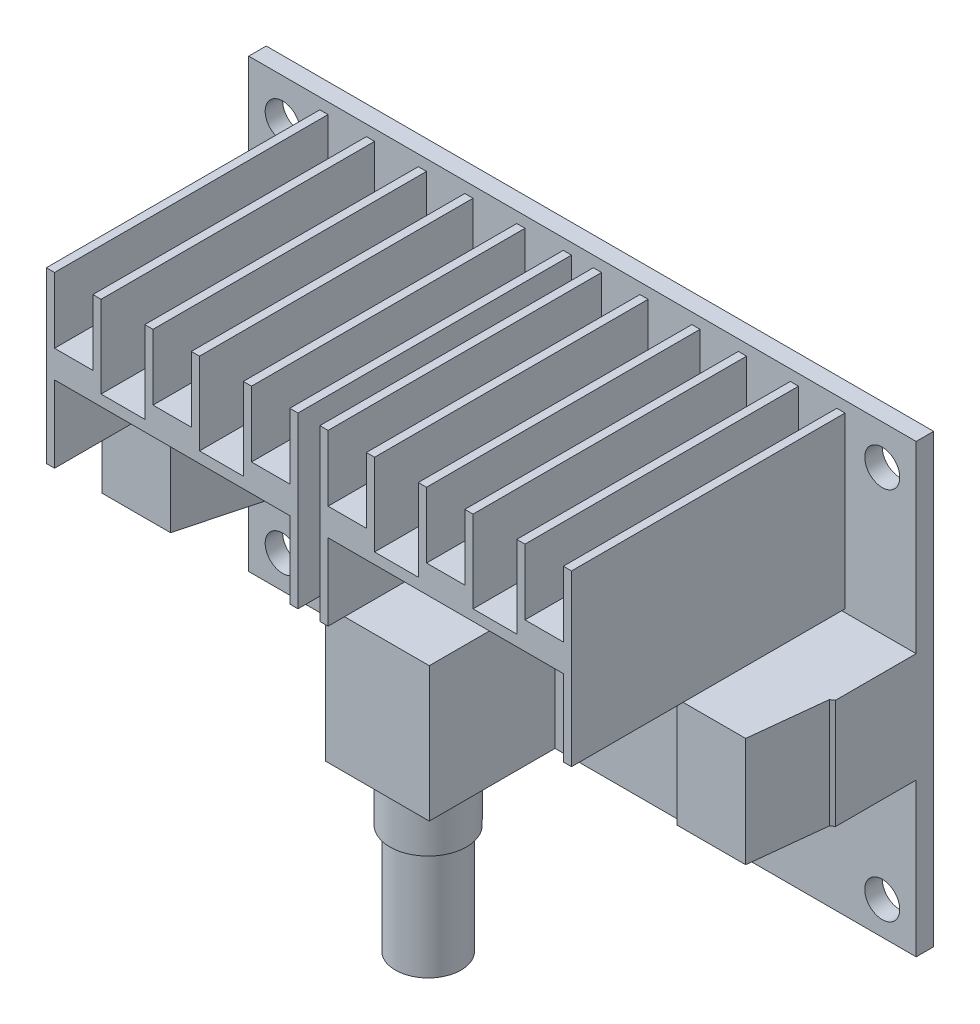
SolidWorks part; units mm, degrees
ref_plane "Front Plane" through (0, 0, 0) normal (0, 0, 1) x (1, 0, 0)
ref_plane "Top Plane" through (0, 0, 0) normal (0, 1, 0) x (1, 0, 0)
ref_plane "Right Plane" through (0, 0, 0) normal (1, 0, 0) x (0, 0, -1)
sketch "Sketch2" plane through (0, 0, 0) normal (0, 0, 1) x (1, 0, 0)
  line L1 (-30.5, -20.4) -> (30.5, -20.4)
  line L2 (-30.5, -20.4) -> (-30.5, 20.4)
  line L3 (-30.5, 20.4) -> (30.5, 20.4)
  line L4 (30.5, -20.4) -> (30.5, 20.4)
  line L5 (-30.5, -20.4) -> (30.5, 20.4) construction
  line L6 (-30.5, 20.4) -> (30.5, -20.4) construction
  circle A0 centre (-27.4, 16.8) radius 1.6
  circle A1 centre (27.4, 16.8) radius 1.6
  circle A2 centre (-27.4, -17.4) radius 1.6
  circle A3 centre (27.4, -17.4) radius 1.6
  point P0 (0, 0)
  dimension "D3" = 3.2
  dimension "D4" = 3.6
  dimension "D5" = 3.1
  dimension "D6" = 3.2
  dimension "D9" = 3.2
  dimension "D10" = 3.2
  dimension "D1" = 61
  dimension "D2" = 40.8
  dimension "D7" = 3.1
  dimension "D8" = 3.6
  dimension "D11" = 3
  dimension "D12" = 3
  dimension "D13" = 3.1
  dimension "D14" = 3.1
extrude "Boss-Extrude1" add sketch "Sketch2" along normal blind 1.6
sketch "Sketch3" plane through (0, 0, 1.6) normal (0, 0, 1) x (1, 0, 0)
  line L0 (-24, 19.4) -> (-24, 3.9)
  line L1 (-24, 3.9) -> (-23.25, 3.9)
  line L2 (-23.25, 3.9) -> (-23.25, 10.9)
  line L3 (-23.25, 10.9) -> (-1.75, 10.9)
  line L4 (-1.75, 10.9) -> (-1.75, 3.9)
  line L5 (-1.75, 3.9) -> (-1, 3.9)
  line L6 (-1, 3.9) -> (-1, 19.4)
  line L7 (-1, 19.4) -> (-1.75, 19.4)
  line L8 (-1.75, 19.4) -> (-1.75, 13.4)
  line L9 (-1.75, 13.4) -> (-5.25, 13.4)
  line L10 (-5.25, 13.4) -> (-5.25, 19.4)
  line L11 (-5.25, 19.4) -> (-6, 19.4)
  line L12 (-6, 19.4) -> (-6, 11.9)
  line L13 (-6, 11.9) -> (-10, 11.9)
  line L14 (-10, 11.9) -> (-10, 19.4)
  line L15 (-10, 19.4) -> (-10.75, 19.4)
  line L16 (-10.75, 19.4) -> (-10.75, 13.4)
  line L17 (-10.75, 13.4) -> (-14.25, 13.4)
  line L18 (-30.5, 20.4) -> (-30.5, -20.4) construction
  line L19 (-15, 19.4) -> (-14.25, 19.4)
  line L20 (-19.75, 19.4) -> (-19, 19.4)
  line L21 (-24, 19.4) -> (-23.25, 19.4)
  line L22 (-23.25, 19.4) -> (-23.25, 13.4)
  line L23 (-23.25, 13.4) -> (-19.75, 13.4)
  line L24 (-19.75, 13.4) -> (-19.75, 19.4)
  line L25 (-19, 19.4) -> (-19, 11.9)
  line L26 (-19, 11.9) -> (-15, 11.9)
  line L27 (-15, 11.9) -> (-15, 19.4)
  line L28 (-14.25, 19.4) -> (-14.25, 13.4)
  line L29 (0, -3.1402) -> (0, -9.8491) construction
  line L30 (30.5, 20.4) -> (-30.5, 20.4) construction
  line L31 (14.25, 19.4) -> (14.25, 13.4)
  line L32 (15, 11.9) -> (15, 19.4)
  line L33 (19, 11.9) -> (15, 11.9)
  line L34 (19, 19.4) -> (19, 11.9)
  line L35 (19.75, 13.4) -> (19.75, 19.4)
  line L36 (23.25, 13.4) -> (19.75, 13.4)
  line L37 (23.25, 19.4) -> (23.25, 13.4)
  line L38 (24, 19.4) -> (23.25, 19.4)
  line L39 (19.75, 19.4) -> (19, 19.4)
  line L40 (15, 19.4) -> (14.25, 19.4)
  line L41 (10.75, 13.4) -> (14.25, 13.4)
  line L42 (10.75, 19.4) -> (10.75, 13.4)
  line L43 (10, 19.4) -> (10.75, 19.4)
  line L44 (10, 11.9) -> (10, 19.4)
  line L45 (6, 11.9) -> (10, 11.9)
  line L46 (6, 19.4) -> (6, 11.9)
  line L47 (5.25, 19.4) -> (6, 19.4)
  line L48 (5.25, 13.4) -> (5.25, 19.4)
  line L49 (1.75, 13.4) -> (5.25, 13.4)
  line L50 (1.75, 19.4) -> (1.75, 13.4)
  line L51 (1, 19.4) -> (1.75, 19.4)
  line L52 (1, 3.9) -> (1, 19.4)
  line L53 (1.75, 3.9) -> (1, 3.9)
  line L54 (1.75, 10.9) -> (1.75, 3.9)
  line L55 (23.25, 10.9) -> (1.75, 10.9)
  line L56 (23.25, 3.9) -> (23.25, 10.9)
  line L57 (24, 3.9) -> (23.25, 3.9)
  line L58 (24, 19.4) -> (24, 3.9)
  point P32 (-12.5, 13.4)
  point P64 (12.5, 13.4)
  dimension "D2" = 0.75
  dimension "D3" = 7
  dimension "D4" = 21.5
  dimension "D5" = 7
  dimension "D6" = 0.75
  dimension "D7" = 15.5
  dimension "D8" = 6
  dimension "D9" = 3.5
  dimension "D10" = 0.75
  dimension "D11" = 6
  dimension "D12" = 7.5
  dimension "D13" = 4
  dimension "D14" = 7.5
  dimension "D15" = 0.75
  dimension "D16" = 6
  dimension "D17" = 0.75
  dimension "D18" = 1
  dimension "D19" = 0.75
  dimension "D20" = 0.75
  dimension "D21" = 15.5
  dimension "D22" = 7.5
  dimension "D23" = 7.5
  dimension "D24" = 6
  dimension "D25" = 2.5
  dimension "D26" = 6.5
  dimension "D27" = 6
  dimension "D28" = 1
  dimension "D29" = 1.75
  dimension "D30" = 4
  dimension "D31" = 3.5
extrude "Boss-Extrude2" add sketch "Sketch3" along normal blind 25
sketch "Sketch5" plane through (0, 0, 1.6) normal (0, 0, 1) x (1, 0, 0)
  line L0 (-30.5, -20.4) -> (30.5, -20.4) construction
  line L1 (-12, -20.4) -> (-2.5, -20.4)
  line L2 (-12, -20.4) -> (-12, -8.1)
  line L3 (-12, -8.1) -> (-2.5, -8.1)
  line L4 (-2.5, -20.4) -> (-2.5, -8.1)
  line L5 (-30.5, 20.4) -> (-30.5, -20.4) construction
  dimension "D1" = 18.5
  dimension "D2" = 9.5
  dimension "D3" = 12.3
extrude "Boss-Extrude3" add sketch "Sketch5" along normal blind 11.5
sketch "Sketch6" plane through (0, -20.4, 0) normal (0, -1, 0) x (1, 0, 0)
  line L0 (-12, 13.1) -> (-12, 1.6) construction
  line L1 (-12, 13.1) -> (-2.5, 13.1) construction
  circle A0 centre (-7.25, 8.45) radius 3.5
  dimension "D1" = 7
  dimension "D2" = 4.75
  dimension "D3" = 4.65
extrude "Boss-Extrude4" add sketch "Sketch6" along normal blind 5
sketch "Sketch7" plane through (0, -25.4, 0) normal (0, -1, 0) x (1, 0, 0)
  circle A0 centre (-7.25, 8.45) radius 3
  circle A1 centre (-7.25, 8.45) radius 3.5 construction
  dimension "D1" = 6
extrude "Boss-Extrude5" add sketch "Sketch7" along normal blind 10
sketch "Sketch8" plane through (0, 0, 1.6) normal (0, 0, 1) x (1, 0, 0)
  line L0 (-30.5, 20.4) -> (-30.5, -20.4) construction
  line L1 (-30.5, 3.6) -> (-20.5, 3.6)
  line L2 (-30.5, 3.6) -> (-30.5, -6.4)
  line L3 (-30.5, -6.4) -> (-20.5, -6.4)
  line L4 (-20.5, 3.6) -> (-20.5, -6.4)
  line L5 (-30.5, -20.4) -> (-12, -20.4) construction
  line L6 (0, -11.9188) -> (0, 0) construction
  line L7 (20.5, 3.6) -> (20.5, -6.4)
  line L8 (30.5, -6.4) -> (20.5, -6.4)
  line L9 (30.5, 3.6) -> (30.5, -6.4)
  line L10 (30.5, 3.6) -> (20.5, 3.6)
  dimension "D1" = 10
  dimension "D2" = 10
  dimension "D3" = 14
extrude "Boss-Extrude6" add sketch "Sketch8" along normal blind 14.5
sketch "Sketch9" plane through (0, -6.4, 0) normal (0, -1, 0) x (1, 0, 0)
  line L0 (-23.151, 16.1) -> (-20.5, 6.1453)
  line L1 (-20.5, 6.1453) -> (-16.2497, 6.0894)
  line L2 (-16.2497, 6.0894) -> (-15.9141, 20.0148)
  line L3 (-15.9141, 20.0148) -> (-23.0951, 19.847)
  line L4 (-23.0951, 19.847) -> (-23.151, 16.1)
  line L5 (-30.5, 16.1) -> (-20.5, 16.1) construction
  line L6 (-20.5, 16.1) -> (-20.5, 1.6) construction
  line L7 (-29.4157, 16.1) -> (-30.1661, 9.2084)
  line L8 (-30.1661, 9.2084) -> (-30.5, 8.9496)
  line L9 (-30.5, 8.9496) -> (-32.8134, 7.8147)
  line L10 (-32.8134, 7.8147) -> (-35.1284, 16.6735)
  line L11 (-35.1284, 16.6735) -> (-30.4363, 21.1049)
  line L12 (-30.4363, 21.1049) -> (-29.4157, 16.1)
  line L13 (-30.5, 16.1) -> (-30.5, 1.6) construction
  line L14 (0, 0) -> (0, 18.2362) construction
  line L15 (30.4363, 21.1049) -> (29.4157, 16.1)
  line L16 (35.1284, 16.6735) -> (30.4363, 21.1049)
  line L17 (32.8134, 7.8147) -> (35.1284, 16.6735)
  line L18 (30.5, 8.9496) -> (32.8134, 7.8147)
  line L19 (30.1661, 9.2084) -> (30.5, 8.9496)
  line L20 (29.4157, 16.1) -> (30.1661, 9.2084)
  line L21 (23.0951, 19.847) -> (23.151, 16.1)
  line L22 (15.9141, 20.0148) -> (23.0951, 19.847)
  line L23 (16.2497, 6.0894) -> (15.9141, 20.0148)
  line L24 (20.5, 6.1453) -> (16.2497, 6.0894)
  line L25 (23.151, 16.1) -> (20.5, 6.1453)
extrude "Cut-Extrude1" cut sketch "Sketch9" against normal blind 10
